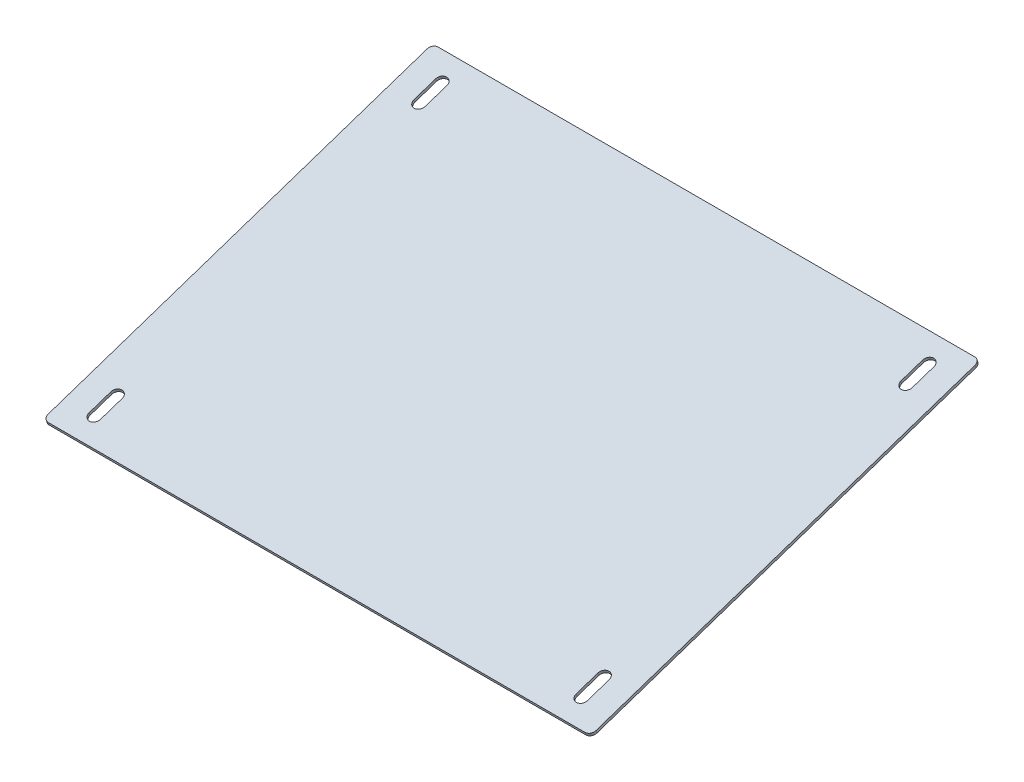
SolidWorks part; units mm, degrees
material "Acrylic (Medium-high impact)"
ref_plane "Front Plane" through (0, 0, 0) normal (0, 0, 1) x (1, 0, 0)
ref_plane "Top Plane" through (0, 0, 0) normal (0, 1, 0) x (1, 0, 0)
ref_plane "Right Plane" through (0, 0, 0) normal (1, 0, 0) x (0, 0, -1)
sketch "Sketch1" plane through (0, 0, 0) normal (1, 0, 0) x (0, 0, -1)
  line L0 (0, 0) -> (75.9126, 25.4)
  line L1 (75.9126, 25.4) -> (75.9126, 0) construction
  line L2 (75.9126, 0) -> (0, 0) construction
  dimension "D1" = 18.5
  dimension "D2" = 25.4
ref_plane "Display Plane" through (0, 0, 0) normal (0, -0.9483, -0.3173) x (0, 0.3173, -0.9483)
sketch "Sketch3" plane through (0, 0, 0) normal (0, -0.9483, -0.3173) x (0, 0.3173, -0.9483)
  line L0 (203.2, -270.9333) -> (203.2, 270.9333) construction
  line L1 (-228.6, 304.8) -> (228.6, 304.8)
  line L2 (-228.6, 304.8) -> (-228.6, -304.8)
  line L3 (-228.6, -304.8) -> (228.6, -304.8)
  line L4 (228.6, 304.8) -> (228.6, -304.8)
  line L5 (-228.6, 304.8) -> (228.6, -304.8) construction
  line L6 (-228.6, -304.8) -> (228.6, 304.8) construction
  line L7 (-203.2, -270.9333) -> (-203.2, 270.9333) construction
  line L8 (203.2, -270.9333) -> (-203.2, -270.9333) construction
  line L9 (203.2, 270.9333) -> (-203.2, 270.9333) construction
  line L10 (228.6, 0) -> (-228.6, 0) construction
  line L11 (0, -304.8) -> (0, 304.8) construction
  line L12 (203.2, -270.9333) -> (177.8, -270.9333) construction
  line L13 (203.2, -277.2833) -> (177.8, -277.2833)
  line L14 (203.2, -264.5833) -> (177.8, -264.5833)
  line L15 (-203.2, -270.9333) -> (-177.8, -270.9333) construction
  line L16 (-203.2, -264.5833) -> (-177.8, -264.5833)
  line L17 (-203.2, -277.2833) -> (-177.8, -277.2833)
  line L18 (203.2, 270.9333) -> (177.8, 270.9333) construction
  line L19 (203.2, 277.2833) -> (177.8, 277.2833)
  line L20 (203.2, 264.5833) -> (177.8, 264.5833)
  line L21 (-203.2, 270.9333) -> (-177.8, 270.9333) construction
  line L22 (-203.2, 264.5833) -> (-177.8, 264.5833)
  line L23 (-203.2, 277.2833) -> (-177.8, 277.2833)
  arc A8 (203.2, -277.2833) -> (203.2, -264.5833) centre (203.2, -270.9333) ccw
  arc A9 (177.8, -264.5833) -> (177.8, -277.2833) centre (177.8, -270.9333) ccw
  arc A10 (-203.2, -264.5833) -> (-203.2, -277.2833) centre (-203.2, -270.9333) ccw
  arc A11 (-177.8, -277.2833) -> (-177.8, -264.5833) centre (-177.8, -270.9333) ccw
  arc A12 (203.2, 277.2833) -> (203.2, 264.5833) centre (203.2, 270.9333) cw
  arc A13 (177.8, 264.5833) -> (177.8, 277.2833) centre (177.8, 270.9333) cw
  arc A14 (-203.2, 264.5833) -> (-203.2, 277.2833) centre (-203.2, 270.9333) cw
  arc A15 (-177.8, 277.2833) -> (-177.8, 264.5833) centre (-177.8, 270.9333) cw
  point P0 (0, 0)
  point P9 (190.5, -270.9333)
  point P20 (-190.5, -270.9333)
  point P27 (190.5, 270.9333)
  point P33 (-190.5, 270.9333)
  dimension "D5" = 6.35
  dimension "D7" = 6.35
  dimension "D1" = 609.6
  dimension "D2" = 457.2
  dimension "D3" = 25.4
  dimension "D4" = 25.4
  dimension "D6" = 25.4
  dimension "D8" = 25.4
extrude "Boss-Extrude1" add sketch "Sketch3" against normal blind 3.175 contours L4 L1 L2 L3 A9 L14 A8 L13
fillet "Fillet1" radius 6.35 4 edges at (-304.8, -71.0304, 217.2905) (-304.8, 74.0413, -216.2831) (304.8, 74.0413, -216.2831) (304.8, -71.0304, 217.2905)
equation "\"D7@Sketch3\"=\"D5@Sketch3\""
equation "\"D8@Sketch3\"=\"D6@Sketch3\""
